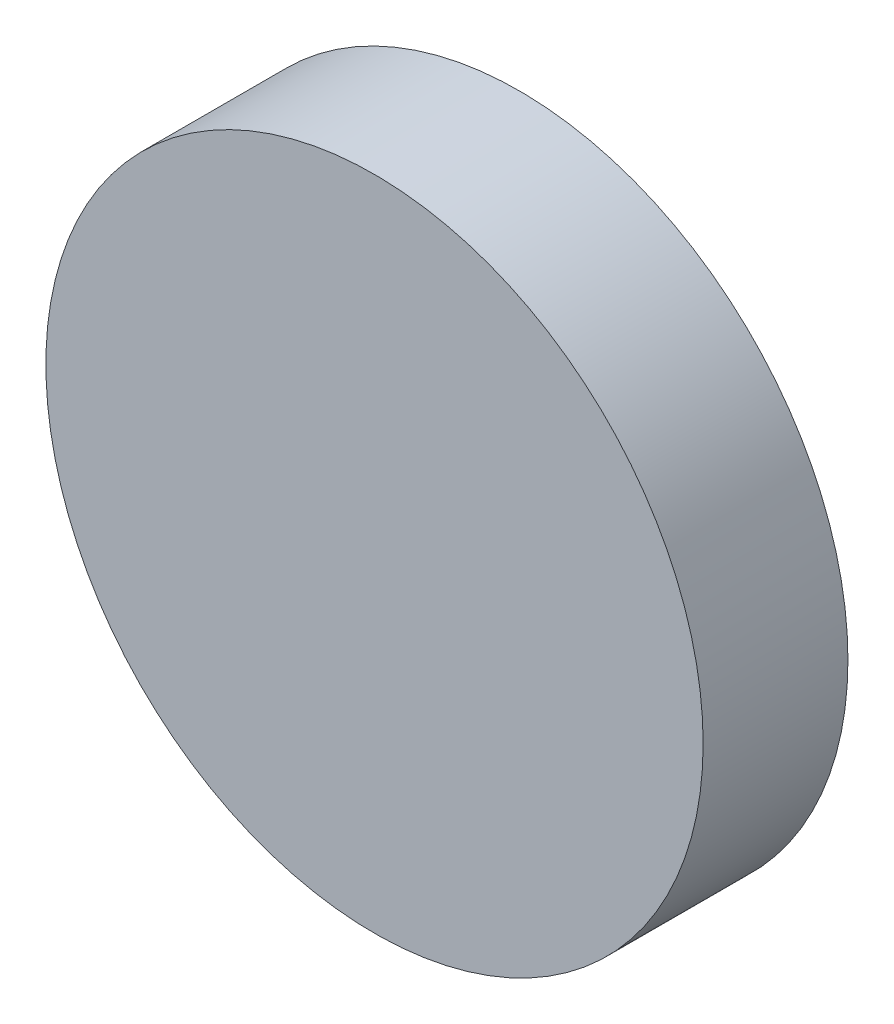
SolidWorks part; units mm, degrees
ref_plane "Front Plane" through (0, 0, 0) normal (0, 0, 1) x (1, 0, 0)
ref_plane "Top Plane" through (0, 0, 0) normal (0, 1, 0) x (1, 0, 0)
ref_plane "Right Plane" through (0, 0, 0) normal (1, 0, 0) x (0, 0, -1)
sketch "Sketch1" plane through (0, 0, 0) normal (0, 0, 1) x (1, 0, 0)
  circle A0 centre (0, 0) radius 22.697
extrude "Boss-Extrude1" add sketch "Sketch1" along normal blind 10
